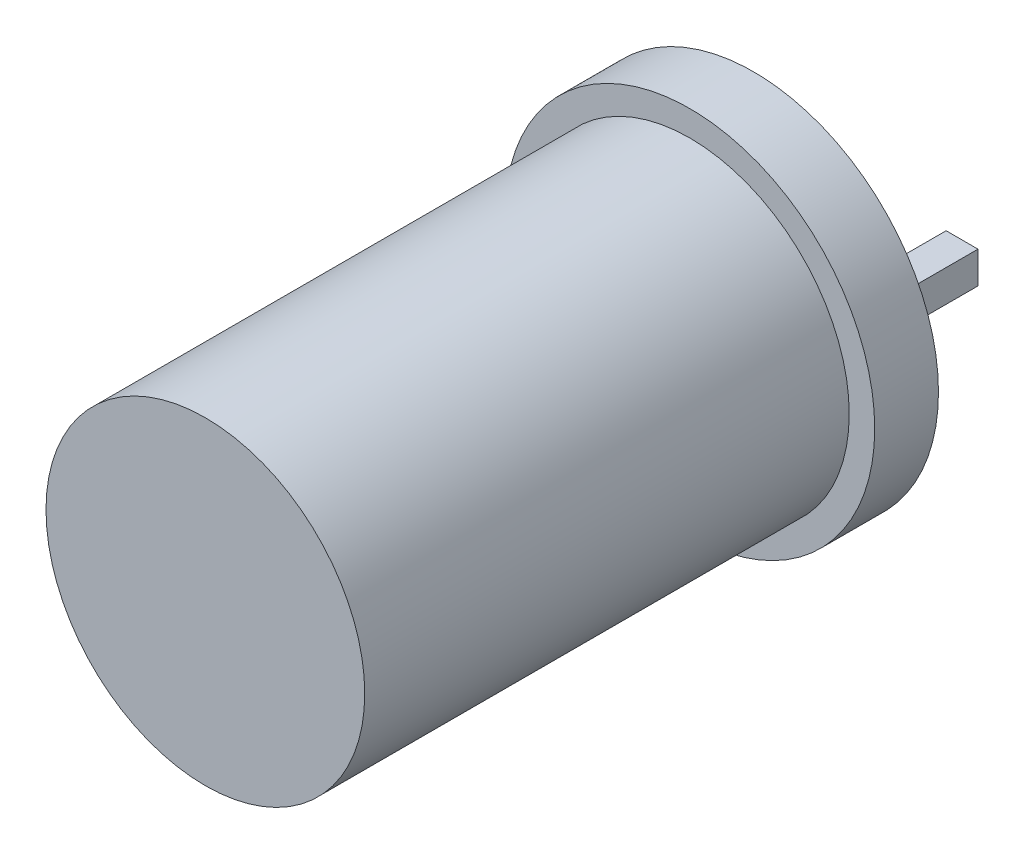
SolidWorks part; units mm, degrees
ref_plane "Front Plane" through (0, 0, 0) normal (0, 0, 1) x (1, 0, 0)
ref_plane "Top Plane" through (0, 0, 0) normal (0, 1, 0) x (1, 0, 0)
ref_plane "Right Plane" through (0, 0, 0) normal (1, 0, 0) x (0, 0, -1)
other "Configuration Table"
sketch "Sketch1" plane through (0, 0, 0) normal (0, 0, 1) x (1, 0, 0)
  circle A0 centre (0, 0) radius 2.5
  dimension "D1" = 5
extrude "Body" add sketch "Sketch1" along normal blind 8.6 from offset 8.6
sketch "Sketch2" plane through (0, 0, 0) normal (0, 0, 1) x (1, 0, 0)
  circle A0 centre (0, 0) radius 2.9
  dimension "D1" = 5.8
extrude "Flange" add sketch "Sketch2" along normal blind 1 from offset 8.6
sketch "Sketch3" plane through (0, 0, 0) normal (0, 0, 1) x (1, 0, 0)
  line L0 (-1.52, -0.25) -> (-1.02, -0.25)
  line L1 (-1.02, -0.25) -> (-1.02, 0.25)
  line L2 (-1.02, 0.25) -> (-1.52, 0.25)
  line L3 (-1.52, 0.25) -> (-1.52, -0.25)
  line L4 (1.02, -0.25) -> (1.52, -0.25)
  line L5 (1.52, -0.25) -> (1.52, 0.25)
  line L6 (1.52, 0.25) -> (1.02, 0.25)
  line L7 (1.02, 0.25) -> (1.02, -0.25)
extrude "Leads" add sketch "Sketch3" against normal blind 2 from offset 8.6
equation "\"Jar_OD\"= 90  'ASSUMED - Part G fallback - jar outer diameter"
equation "\"Jar_H\"= 120  'ASSUMED - Part G fallback - jar height"
equation "\"Pump_L\"= 45  'ASSUMED - Part G fallback"
equation "\"Pump_W\"= 24  'ASSUMED - Part G fallback"
equation "\"Pump_H\"= 33  'ASSUMED - Part G fallback"
equation "\"Pump_Outlet_OD\"= 7.5  'ASSUMED - Part G fallback"
equation "\"Tube_OD\"= 8  'ASSUMED - Part G fallback"
equation "\"Tube_ID\"= 6  'ASSUMED - Part G fallback"
equation "\"TDS_Body_Dia\"= 12  'ASSUMED - Part G fallback"
equation "\"TDS_Wet_Len\"= 45  'ASSUMED - Part G fallback - length in water"
equation "\"DS_Tube_Dia\"= 6  'ASSUMED - Part G fallback"
equation "\"DS_Tube_Len\"= 50  'ASSUMED - Part G fallback"
equation "\"ORP_Body_Dia\"= 12  'ASSUMED - Part G fallback"
equation "\"ORP_Body_Len\"= 150  'ASSUMED - Part G fallback"
equation "\"ORP_Cap_Dia\"= 16  'ASSUMED - Part G fallback"
equation "\"Turb_W\"= 33  'ASSUMED - Part G fallback - head width"
equation "\"Turb_D\"= 28  'ASSUMED - Part G fallback - head depth"
equation "\"Turb_H\"= 30  'ASSUMED - Part G fallback - head height"
equation "\"Turb_Slot_W\"= 10  'ASSUMED - Part G fallback - slot width"
equation "\"Flow_L\"= 62  'ASSUMED - Part G fallback YF-S201"
equation "\"Flow_W\"= 36  'ASSUMED - Part G fallback"
equation "\"Flow_H\"= 35  'ASSUMED - Part G fallback"
equation "\"Thread_G12_OD\"= 20.955  'ASSUMED - Part G fallback thread G1/2 (major diameter)"
equation "\"Valve_L\"= 75  'ASSUMED - Part G fallback"
equation "\"Valve_W\"= 45  'ASSUMED - Part G fallback"
equation "\"Valve_H\"= 60  'ASSUMED - Part G fallback"
equation "\"Tee_L\"= 40  'ASSUMED - Part G fallback - overall length"
equation "\"Tee_Branch_L\"= 25  'ASSUMED - Part G fallback"
equation "\"Tee_OD\"= 12  'ASSUMED - Part G fallback"
equation "\"LED_Board_L\"= 20  'ASSUMED - Part G fallback"
equation "\"LED_Board_W\"= 20  'ASSUMED - Part G fallback - LED at centre"
equation "\"GUVA_L\"= 20  'ASSUMED - Part G fallback"
equation "\"GUVA_W\"= 12  'ASSUMED - Part G fallback - sensor at centre"
equation "\"Reed_L\"= 27  'ASSUMED - Part G fallback MC-38 half"
equation "\"Reed_W\"= 14  'ASSUMED - Part G fallback"
equation "\"Reed_H\"= 8  'ASSUMED - Part G fallback"
equation "\"ESP_L\"= 51  'ASSUMED - Part G fallback"
equation "\"ESP_W\"= 28  'ASSUMED - Part G fallback"
equation "\"TFT_L\"= 58  'ASSUMED - Part G fallback - board"
equation "\"TFT_W\"= 35  'ASSUMED - Part G fallback - board"
equation "\"TFT_Win_L\"= 35  'ASSUMED - Part G fallback - visible window"
equation "\"TFT_Win_W\"= 28  'ASSUMED - Part G fallback - visible window"
equation "\"Relay_L\"= 50  'ASSUMED - Part G fallback"
equation "\"Relay_W\"= 26  'ASSUMED - Part G fallback"
equation "\"Relay_H\"= 19  'ASSUMED - Part G fallback"
equation "\"Mosfet_L\"= 34  'ASSUMED - Part G fallback"
equation "\"Mosfet_W\"= 17  'ASSUMED - Part G fallback"
equation "\"Mosfet_H\"= 12  'ASSUMED - Part G fallback"
equation "\"TDS_Board_L\"= 42  'ASSUMED - Part G fallback"
equation "\"TDS_Board_W\"= 32  'ASSUMED - Part G fallback"
equation "\"Turb_Board_L\"= 38  'ASSUMED - Part G fallback"
equation "\"Turb_Board_W\"= 28  'ASSUMED - Part G fallback"
equation "\"BNC_Thread_Dia\"= 9.5  'ASSUMED - Part G fallback"
equation "\"Plate_L\"= 420  'ASSUMED - Part G fallback"
equation "\"Plate_W\"= 297  'ASSUMED - Part G fallback"
equation "\"Plate_T\"= 6  'ASSUMED - Part G fallback"
equation "\"Booster_L\"= 150  'ASSUMED - Part G fallback - booster pump"
equation "\"Booster_W\"= 95  'ASSUMED - Part G fallback"
equation "\"Booster_H\"= 100  'ASSUMED - Part G fallback"
equation "\"PTube_OD\"= 6.35  'ASSUMED - Part G fallback - product tube 1/4 inch"
equation "\"Qz_Out\"= 12  'ASSUMED - Part G fallback - quartz channel outside square"
equation "\"Qz_Path\"= 10  'ASSUMED - Part G fallback - quartz channel inside light path"
equation "\"Qz_L\"= 40  'ASSUMED - Part G fallback - quartz channel length"
equation "\"LED860_Dia\"= 5  'ASSUMED - Part G fallback - 860 nm LED"
equation "\"BPW_L\"= 5.4  'ASSUMED - Part G fallback - BPW34"
equation "\"BPW_W\"= 4.3  'ASSUMED - Part G fallback - BPW34"
equation "\"Cart_Dia\"= 50  'ASSUMED - Part G fallback - sediment and pre-carbon cartridges"
equation "\"Cart_L\"= 255  'ASSUMED - Part G fallback"
equation "\"UF_Dia\"= 50  'ASSUMED - Part G fallback - UF cartridge"
equation "\"UF_L\"= 260  'ASSUMED - Part G fallback"
equation "\"RO_Dia\"= 62  'ASSUMED - Part G fallback - RO membrane housing"
equation "\"RO_L\"= 300  'ASSUMED - Part G fallback"
equation "\"UVC_Dia\"= 40  'ASSUMED - Part G fallback - UV-C chamber"
equation "\"UVC_L\"= 300  'ASSUMED - Part G fallback"
equation "\"Tank_W\"= 260  'ASSUMED - Part G fallback - storage tank"
equation "\"Tank_D\"= 160  'ASSUMED - Part G fallback"
equation "\"Tank_H\"= 300  'ASSUMED - Part G fallback"
equation "\"Cab_W\"= 400  'ASSUMED - Part G fallback - purifier cabinet"
equation "\"Cab_D\"= 270  'ASSUMED - Part G fallback"
equation "\"Cab_H\"= 560  'ASSUMED - Part G fallback"
equation "\"ORP_Board_L\"= 40  'ASSUMED - Part G fallback - ORP buffer board"
equation "\"ORP_Board_W\"= 30  'ASSUMED - Part G fallback"
equation "\"Opt_Board_L\"= 50  'ASSUMED - Part G fallback - optical front-end board"
equation "\"Opt_Board_W\"= 40  'ASSUMED - Part G fallback"
equation "\"Buck_L\"= 43  'ASSUMED - Part G fallback - 12 V to 5 V buck module"
equation "\"Buck_W\"= 21  'ASSUMED - Part G fallback"
equation "\"Buck_H\"= 14  'ASSUMED - Part G fallback"
equation "\"BB_L\"= 165  'ASSUMED - Part G fallback - breadboard (As_Built_R3 only)"
equation "\"BB_W\"= 55  'ASSUMED - Part G fallback"
equation "\"BB_H\"= 10  'ASSUMED - Part G fallback"
equation "\"Cuv_W\"= 12.5  'ASSUMED - old R3 cuvette (station suppressed in SS4)"
equation "\"Cuv_D\"= 12.5  'ASSUMED - old R3 cuvette (station suppressed in SS4)"
equation "\"Cuv_H\"= 45  'ASSUMED - old R3 cuvette (station suppressed in SS4)"
equation "\"Probe_Clr\"= 0.3  'DESIGN VALUE - Part C rule 3 - printed probe hole = diameter + 0.3"
equation "\"Label_H\"= 0.6  'DESIGN VALUE - Part D - raised label height"
equation "\"D1@Sketch1\" = \"LED860_Dia\""
